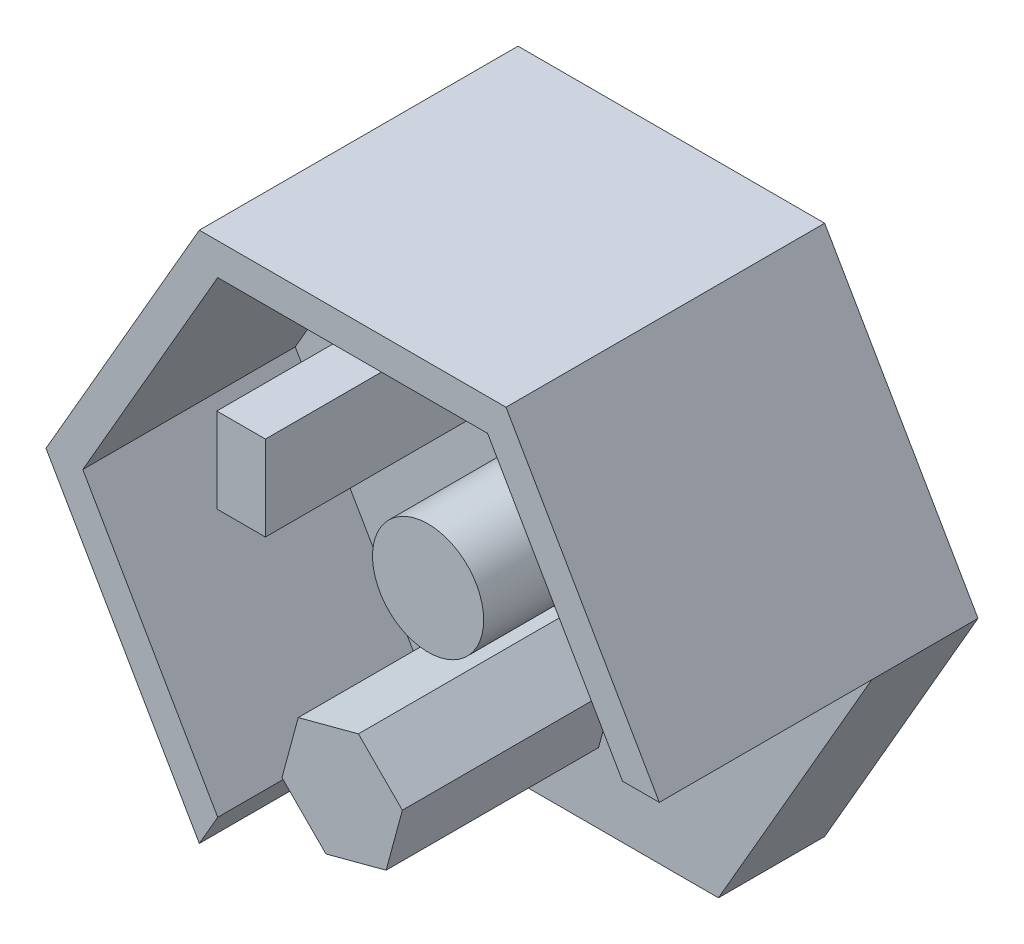
SolidWorks part; units mm, degrees
ref_plane "Front Plane" through (0, 0, 0) normal (0, 0, 1) x (1, 0, 0)
ref_plane "Top Plane" through (0, 0, 0) normal (0, 1, 0) x (1, 0, 0)
ref_plane "Right Plane" through (0, 0, 0) normal (1, 0, 0) x (0, 0, -1)
sketch "Sketch1" plane through (0, 0, 0) normal (0, 0, 1) x (1, 0, 0)
  line L1 (144.3376, -250) -> (288.6751, 0)
  line L2 (288.6751, 0) -> (144.3376, 250)
  line L3 (144.3376, 250) -> (-144.3376, 250)
  line L4 (-144.3376, 250) -> (-288.6751, 0)
  line L5 (-288.6751, 0) -> (-144.3376, -250)
  line L6 (-144.3376, -250) -> (144.3376, -250)
  circle A0 centre (0, 0) radius 250 construction
  dimension "D1" = 500
extrude "Boss-Extrude1" add sketch "Sketch1" along normal blind 300
sketch "Sketch2" plane through (0, 0, 300) normal (0, 0, 1) x (1, 0, 0)
  line L0 (288.6751, 0) -> (144.3376, 250) construction
  line L1 (254.0341, 0) -> (127.0171, 220)
  line L2 (127.0171, 220) -> (-127.0171, 220)
  line L3 (-127.0171, 220) -> (-254.0341, 0)
  line L4 (-254.0341, 0) -> (-127.0171, -220)
  line L5 (-127.0171, -220) -> (127.0171, -220)
  line L6 (127.0171, -220) -> (254.0341, 0)
  circle A0 centre (0, 0) radius 220 construction
  dimension "D1" = 30
extrude "Cut-Extrude1" cut sketch "Sketch2" against normal blind 200
sketch "Sketch3" plane through (0, 0, 300) normal (0, 0, 1) x (1, 0, 0)
  line L0 (-127.0171, -220) -> (-144.3376, -250)
  line L1 (-288.6751, 0) -> (-144.3376, -250) construction
  line L2 (-144.3376, -250) -> (144.3376, -250) construction
  line L3 (-144.3376, -250) -> (-253.0981, -358.1577)
  line L4 (-253.0981, -358.1577) -> (520.5226, -384.9002)
  line L5 (520.5226, -384.9002) -> (552.9955, 34.3831)
  line L6 (552.9955, 34.3831) -> (288.6751, 0)
  line L7 (288.6751, 0) -> (254.0341, 0)
  line L8 (254.0341, 0) -> (-127.0171, -220)
extrude "Cut-Extrude2" cut sketch "Sketch3" against normal up to surface (200 mm away) up to face at (0, 0, 100)
sketch "Sketch4" plane through (0, 0, 100) normal (0, 0, 1) x (1, 0, 0)
  line L1 (-127.8735, 110.808) -> (-82.0971, 110.808)
  line L2 (-127.8735, 110.808) -> (-127.8735, 30.9238)
  line L3 (-127.8735, 30.9238) -> (-82.0971, 30.9238)
  line L4 (-82.0971, 110.808) -> (-82.0971, 30.9238)
  circle A0 centre (71, 65.9084) radius 52.3235
extrude "Boss-Extrude2" add sketch "Sketch4" along normal blind 200
sketch "Sketch5" plane through (0, 0, 100) normal (0, 0, 1) x (1, 0, 0)
  line L1 (46.7934, -127.3096) -> (5.4202, -85.7645)
  line L2 (5.4202, -85.7645) -> (-51.2455, -100.8222)
  line L3 (-51.2455, -100.8222) -> (-66.538, -157.425)
  line L4 (-66.538, -157.425) -> (-25.1648, -198.9701)
  line L5 (-25.1648, -198.9701) -> (31.5009, -183.9124)
  line L6 (31.5009, -183.9124) -> (46.7934, -127.3096)
  circle A0 centre (-9.8723, -142.3673) radius 50.777 construction
extrude "Boss-Extrude3" add sketch "Sketch5" along normal blind 200
